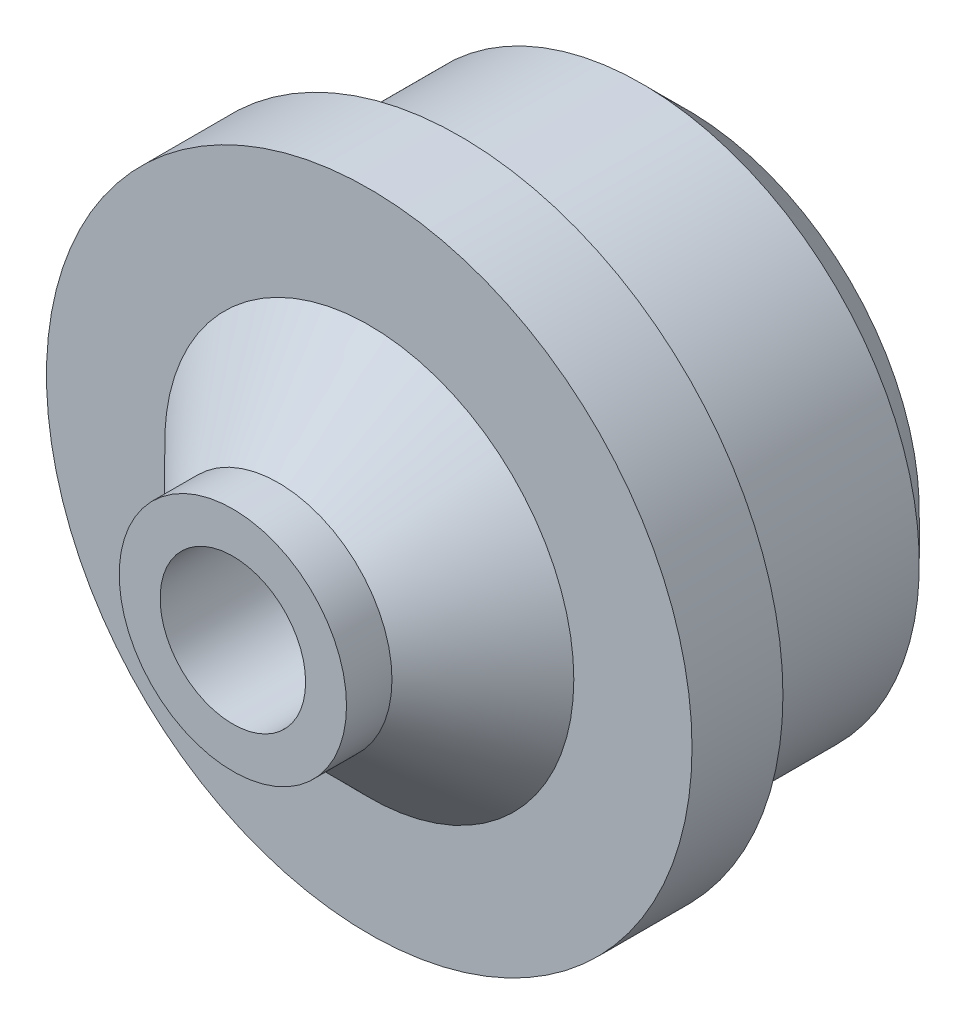
SolidWorks part; units mm, degrees
ref_plane "正面" through (0, 0, 0) normal (0, 0, 1) x (1, 0, 0)
ref_plane "平面" through (0, 0, 0) normal (0, 1, 0) x (1, 0, 0)
ref_plane "右側面" through (0, 0, 0) normal (1, 0, 0) x (0, 0, -1)
sketch "ｽｹｯﾁ1" plane through (0, 0, 0) normal (0, 0, 1) x (1, 0, 0)
  line L3 (-6.0369, 0.875) -> (-6.35, 0.875)
  line L4 (-6.35, -0.875) -> (-6.0369, -0.875)
  line L5 (-6.35, 0.875) -> (-6.35, -0.875)
  line L6 (-6.0369, 0.875) -> (-6.35, 0.875)
  line L7 (-6.35, -0.875) -> (-6.0369, -0.875)
  line L8 (-6.35, 0.875) -> (-6.35, -0.875)
  circle A1 centre (0, 0) radius 7.1
  circle A2 centre (0, 0) radius 7.1
  arc A3 (-6.0369, -0.875) -> (-6.0369, 0.875) centre (0, 0) ccw
  arc A4 (-6.0369, -0.875) -> (-6.0369, 0.875) centre (0, 0) ccw
  dimension "D1" = 0
  dimension "D2" = 0
extrude "ﾎﾞｽ - 押し出し1" add sketch "ｽｹｯﾁ1" against normal blind 5 contours L7 A4 L6 L8
sketch "ｽｹｯﾁ2" plane through (0, 0, 0) normal (0, 0, 1) x (1, 0, 0)
  circle A1 centre (0, 0) radius 7.1
  circle A2 centre (0, 0) radius 7.1
  dimension "D1" = 0
extrude "ﾎﾞｽ - 押し出し2" add sketch "ｽｹｯﾁ2" along normal blind 2
sketch "ｽｹｯﾁ3" plane through (0, 0, 2) normal (0, 0, 1) x (1, 0, 0)
  circle A0 centre (0, 0) radius 2.5
  dimension "D1" = 5
extrude "ﾎﾞｽ - 押し出し3" add sketch "ｽｹｯﾁ3" along normal blind 7
chamfer "面取り1" distance 2 angle 45 1 edges at (2.5, 0, 2)
sketch "ｽｹｯﾁ4" plane through (0, 0, 9) normal (0, 0, 1) x (1, 0, 0)
  circle A0 centre (0, 0) radius 1.6
  dimension "D1" = 3.2
extrude "ｶｯﾄ - 押し出し1" cut sketch "ｽｹｯﾁ4" against normal blind 30
chamfer "面取り2" distance 1 angle 45 1 edges at (6.1, 0, -5)
other "面の移動1" face at (1.6, 0, 9) parameters "D1"=4
sketch "ｽｹｯﾁ5" plane through (0, 0, 0) normal (1, 0, 0) x (0, 0, -1)
  line L0 (-4, -2.5) -> (-5, -2.5)
  line L1 (-5, 2.5) -> (-4, 2.5)
  line L2 (-5, 2.5) -> (-4, 2.5) construction
  line L3 (-4, -2.5) -> (-5, -2.5) construction
  line L4 (-2, -4.5) -> (-4, -2.5)
  line L5 (-4, 2.5) -> (-2, 4.5)
  line L6 (-4, 2.5) -> (-2, 4.5) construction
  line L7 (-2, -4.5) -> (-4, -2.5) construction
  line L8 (-5, 2.5) -> (-5, -2.5) construction
